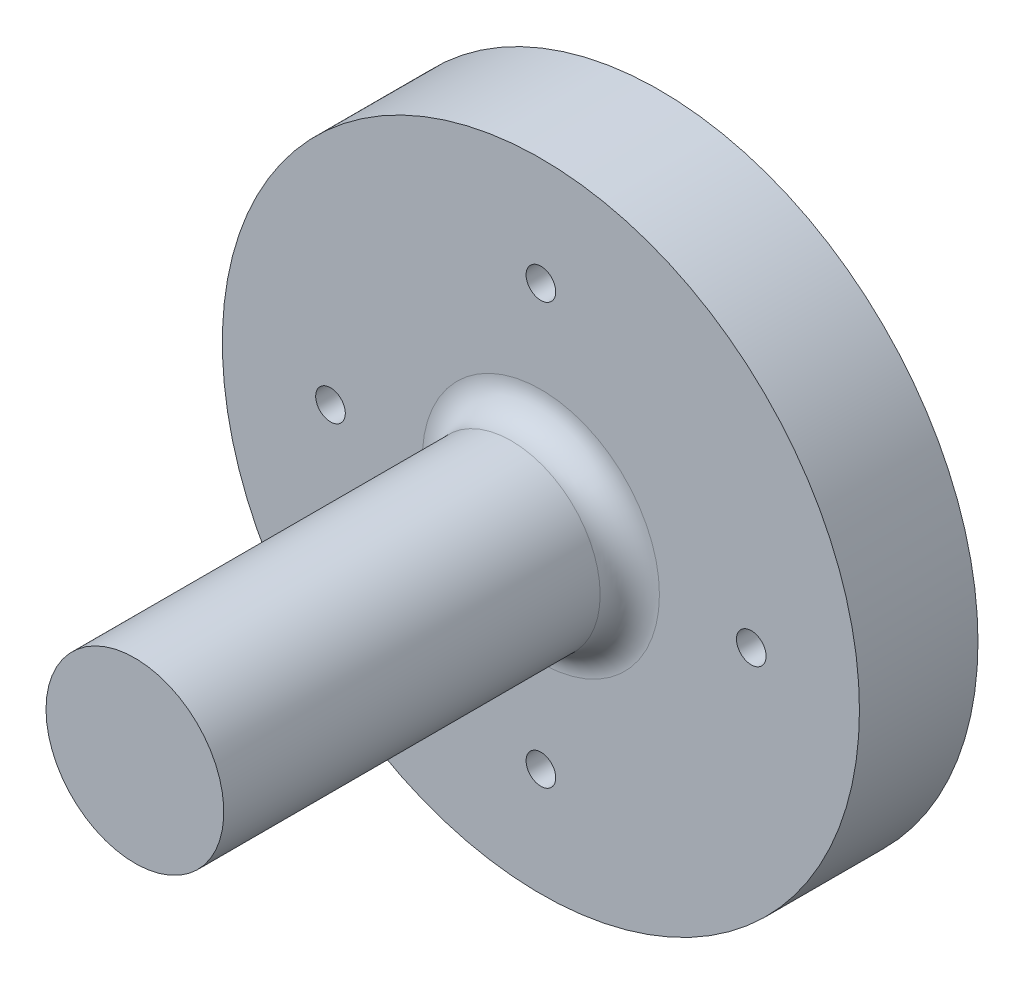
SolidWorks part; units mm, degrees
ref_plane "Plano frontal" through (0, 0, 0) normal (0, 0, 1) x (1, 0, 0)
ref_plane "Plano superior" through (0, 0, 0) normal (0, 1, 0) x (1, 0, 0)
ref_plane "Plano direito" through (0, 0, 0) normal (1, 0, 0) x (0, 0, -1)
sketch "Esboço1" plane through (0, 0, 0) normal (0, 0, 1) x (1, 0, 0)
  circle A0 centre (0, 0) radius 10.75
  dimension "D1" = 21.5
extrude "Ressalto-extrusão1" add sketch "Esboço1" along normal blind 4
sketch "Esboço2" plane through (0, 0, 4) normal (0, 0, 1) x (1, 0, 0)
  circle A0 centre (0, 0) radius 3
  dimension "D1" = 6
extrude "Ressalto-extrusão2" add sketch "Esboço2" along normal blind 13.7
fillet "Filete2" radius 1 1 edges at (3, 0, 4)
sketch "Esboço3" plane through (0, 0, 4) normal (0, 0, 1) x (1, 0, 0)
  circle A0 centre (7.1, 0) radius 0.5
  circle A1 centre (-7.1, 0) radius 0.5
  circle A2 centre (0, 7.1) radius 0.5
  circle A3 centre (0, -7.1) radius 0.5
  dimension "D1" = 1
  dimension "D2" = 1
  dimension "D3" = 14.2
  dimension "D4" = 7.1
  dimension "D5" = 1
  dimension "D6" = 1
  dimension "D7" = 7.1
  dimension "D8" = 14.2
extrude "Corte-extrusão1" cut sketch "Esboço3" against normal through all
